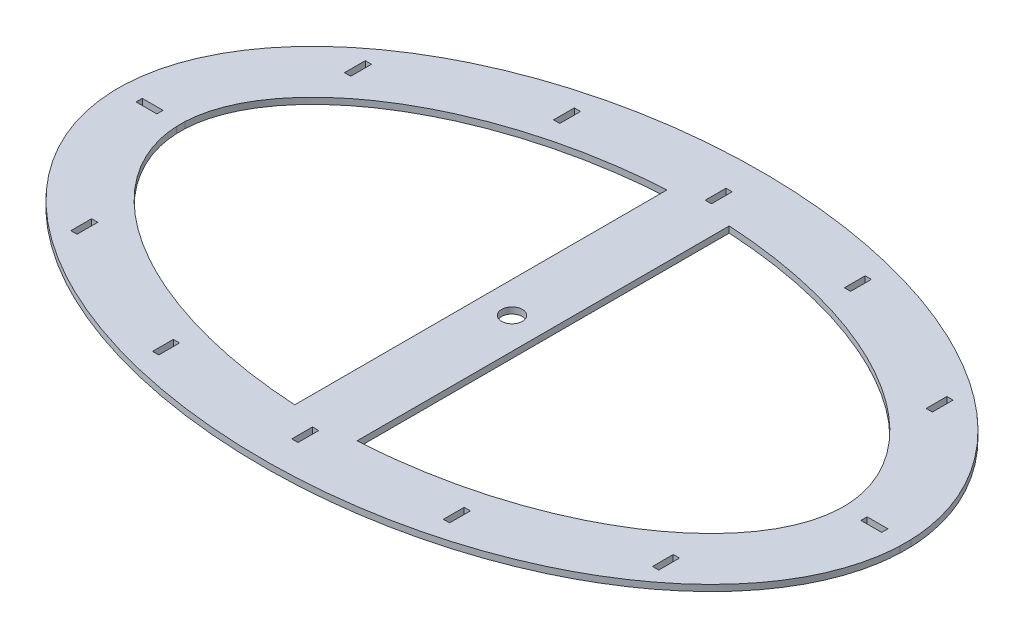
SolidWorks part; units mm, degrees
ref_plane "前视基准面" through (0, 0, 0) normal (0, 0, 1) x (1, 0, 0)
ref_plane "上视基准面" through (0, 0, 0) normal (0, 1, 0) x (1, 0, 0)
ref_plane "右视基准面" through (0, 0, 0) normal (1, 0, 0) x (0, 0, -1)
sketch "草图1" plane through (0, 0, 0) normal (0, 1, 0) x (1, 0, 0)
  line L0 (159.5, 2.0834) -> (159.5, -2.0834)
  line L1 (-189.5, 2.6781) -> (-189.5, -2.6781)
  line L2 (189.5, 2.6781) -> (189.5, -2.6781)
  line L3 (-159.5, 2.0834) -> (-159.5, -2.0834)
  line L6 (-15, -89.5841) -> (-15, 89.5841)
  line L8 (15, -89.5841) -> (15, 89.5841)
  circle A0 centre (0, 0) radius 5
  spline S0 degree 4 poles (-189.5, 2.6781) (-189.403, 5.4288) (-188.9135, 11.2804) (-187.1848, 20.477) (-182.9016, 32.5585) (-176.5181, 44.4734) (-168.3707, 55.661) (-158.8165, 65.9375) (-145.6224, 77.4085) (-128.2334, 89.1222) (-106.4053, 100.093) (-80.3284, 109.3456) (-53.4155, 115.7167) (-26.0125, 119.4067) (1.6122, 120.5267) (29.2235, 119.1102) (56.5842, 115.1149) (83.4196, 108.4201) (109.201, 98.8767) (130.5275, 87.757) (147.4252, 76.0011) (160.1728, 64.5989) (169.4507, 54.338) (177.4202, 43.0195) (183.4223, 31.3068) (187.3852, 19.5711) (188.9582, 10.7853) (189.4055, 5.3595) (189.5, 2.6781) knots 0 0 0 0 0 0.022605 0.04819 0.076526 0.104867 0.133209 0.161552 0.191528 0.248215 0.304901 0.361588 0.418275 0.474961 0.531648 0.588335 0.645021 0.701708 0.758395 0.813601 0.841944 0.870287 0.89863 0.926971 0.955318 0.977964 1 1 1 1 1 construction
  spline S1 degree 4 poles (-189.5, 2.6781) (-189.403, 5.4288) (-188.9135, 11.2804) (-187.1848, 20.477) (-182.9016, 32.5585) (-176.5181, 44.4734) (-168.3707, 55.661) (-158.8165, 65.9375) (-145.6224, 77.4085) (-128.2334, 89.1222) (-106.4053, 100.093) (-80.3284, 109.3456) (-53.4155, 115.7167) (-26.0125, 119.4067) (1.6122, 120.5267) (29.2235, 119.1102) (56.5842, 115.1149) (83.4196, 108.4201) (109.201, 98.8767) (130.5275, 87.757) (147.4252, 76.0011) (160.1728, 64.5989) (169.4507, 54.338) (177.4202, 43.0195) (183.4223, 31.3068) (187.3852, 19.5711) (188.9582, 10.7853) (189.4055, 5.3595) (189.5, 2.6781) knots 0 0 0 0 0 0.022605 0.04819 0.076526 0.104867 0.133209 0.161552 0.191528 0.248215 0.304901 0.361588 0.418275 0.474961 0.531648 0.588335 0.645021 0.701708 0.758395 0.813601 0.841944 0.870287 0.89863 0.926971 0.955318 0.977964 1 1 1 1 1
  spline S2 degree 4 poles (-189.5, -2.6781) (-189.403, -5.4288) (-188.9135, -11.2804) (-187.1848, -20.477) (-182.9016, -32.5585) (-176.5181, -44.4734) (-168.3707, -55.661) (-158.8165, -65.9375) (-145.6224, -77.4085) (-128.2334, -89.1222) (-106.4053, -100.093) (-80.3284, -109.3456) (-53.4155, -115.7167) (-26.0125, -119.4067) (1.6122, -120.5267) (29.2235, -119.1102) (56.5842, -115.1149) (83.4196, -108.4201) (109.201, -98.8767) (130.5275, -87.757) (147.4252, -76.0011) (160.1728, -64.5989) (169.4507, -54.338) (177.4202, -43.0195) (183.4223, -31.3068) (187.3852, -19.5711) (188.9582, -10.7853) (189.4055, -5.3595) (189.5, -2.6781) knots 0 0 0 0 0 0.022605 0.04819 0.076526 0.104867 0.133209 0.161552 0.191528 0.248215 0.304901 0.361588 0.418275 0.474961 0.531648 0.588335 0.645021 0.701708 0.758395 0.813601 0.841944 0.870287 0.89863 0.926971 0.955318 0.977964 1 1 1 1 1
  spline S3 degree 1 poles (-159.5, 2.0834) (159.5, 2.0834) knots 0 0 1 1 construction
  spline S4 degree 1 poles (-159.5, -2.0834) (159.5, -2.0834) knots 0 0 1 1 construction
  spline S5 degree 3 poles (-159.5, 2.0834) (-159.4304, 3.6198) (-159.1394, 6.6713) (-157.9407, 12.8162) (-155.2804, 20.5003) (-150.2462, 29.6305) (-141.2678, 41.3756) (-126.3637, 54.7415) (-104.5151, 67.8369) (-80.1382, 77.8661) (-54.1823, 84.9094) (-27.3041, 89.0816) (0, 90.4628) (27.3041, 89.0816) (54.1823, 84.9094) (80.1382, 77.8661) (104.5153, 67.8369) (126.3637, 54.7414) (141.2676, 41.3759) (150.2464, 29.6301) (155.2803, 20.5005) (157.9408, 12.816) (159.1394, 6.6715) (159.4304, 3.6198) (159.5, 2.0834) knots 0.001569 0.001569 0.001569 0.001569 0.017145 0.032721 0.063873 0.095025 0.126177 0.18848 0.250784 0.313088 0.375392 0.437696 0.5 0.562304 0.624608 0.686912 0.749216 0.81152 0.873823 0.904975 0.936127 0.967279 0.982855 0.998431 0.998431 0.998431 0.998431
  spline S6 degree 3 poles (159.5, -2.0834) (159.4304, -3.6198) (159.1394, -6.6715) (157.9408, -12.816) (155.2803, -20.5005) (150.2464, -29.6301) (141.2676, -41.3759) (126.3637, -54.7414) (104.5153, -67.8369) (80.1382, -77.8661) (54.1823, -84.9094) (27.3041, -89.0816) (0, -90.4628) (-27.3041, -89.0816) (-54.1823, -84.9094) (-80.1382, -77.8661) (-104.5151, -67.8369) (-126.3637, -54.7415) (-141.2678, -41.3756) (-150.2462, -29.6305) (-155.2804, -20.5003) (-157.9407, -12.8162) (-159.1394, -6.6713) (-159.4304, -3.6198) (-159.5, -2.0834) knots 0.001569 0.001569 0.001569 0.001569 0.017145 0.032721 0.063873 0.095025 0.126177 0.18848 0.250784 0.313088 0.375392 0.437696 0.5 0.562304 0.624608 0.686912 0.749216 0.81152 0.873823 0.904975 0.936127 0.967279 0.982855 0.998431 0.998431 0.998431 0.998431
  point P11 (0, 0)
  dimension "D1" = 30
extrude "凸台-拉伸1" add sketch "草图1" along normal blind 3 contours S6 L8 S5 L6 A0 | L1 S2 L2 S1 L0 S6 L3 S5
sketch "草图2" plane through (0, 3, 0) normal (0, 1, 0) x (1, 0, 0)
  line L1 (141.5, -70.874) -> (138.5, -70.874)
  line L2 (141.5, -70.874) -> (141.5, -60.874)
  line L3 (141.5, -60.874) -> (138.5, -60.874)
  line L4 (138.5, -70.874) -> (138.5, -60.874)
  line L5 (179.4735, -1.5024) -> (169.4735, -1.5024)
  line L6 (179.4735, -1.5024) -> (179.4735, 1.4976)
  line L7 (179.4735, 1.4976) -> (169.4735, 1.4976)
  line L8 (169.4735, -1.5024) -> (169.4735, 1.4976)
  line L9 (141.5, 60.8692) -> (138.5, 60.8692)
  line L10 (141.5, 60.8692) -> (141.5, 70.8692)
  line L11 (141.5, 70.8692) -> (138.5, 70.8692)
  line L12 (138.5, 60.8692) -> (138.5, 70.8692)
  line L13 (71.5, -101.514) -> (68.5, -101.514)
  line L14 (71.5, -101.514) -> (71.5, -91.514)
  line L15 (71.5, -91.514) -> (68.5, -91.514)
  line L16 (68.5, -101.514) -> (68.5, -91.514)
  line L17 (71.5, 91.5092) -> (68.5, 91.5092)
  line L18 (71.5, 91.5092) -> (71.5, 101.5092)
  line L19 (71.5, 101.5092) -> (68.5, 101.5092)
  line L20 (68.5, 91.5092) -> (68.5, 101.5092)
  line L21 (1.5, 94.5195) -> (-1.5, 94.5195)
  line L22 (1.5, 94.5195) -> (1.5, 104.5195)
  line L23 (1.5, 104.5195) -> (-1.5, 104.5195)
  line L24 (-1.5, 94.5195) -> (-1.5, 104.5195)
  line L25 (1.5, -104.5243) -> (-1.5, -104.5243)
  line L26 (1.5, -104.5243) -> (1.5, -94.5243)
  line L27 (1.5, -94.5243) -> (-1.5, -94.5243)
  line L28 (-1.5, -104.5243) -> (-1.5, -94.5243)
  line L29 (-68.5, -101.514) -> (-71.5, -101.514)
  line L30 (-68.5, -101.514) -> (-68.5, -91.514)
  line L31 (-68.5, -91.514) -> (-71.5, -91.514)
  line L32 (-71.5, -101.514) -> (-71.5, -91.514)
  line L33 (-138.5, -70.874) -> (-141.5, -70.874)
  line L34 (-138.5, -70.874) -> (-138.5, -60.874)
  line L35 (-138.5, -60.874) -> (-141.5, -60.874)
  line L36 (-141.5, -70.874) -> (-141.5, -60.874)
  line L37 (-169.4735, -1.5024) -> (-179.4735, -1.5024)
  line L38 (-169.4735, -1.5024) -> (-169.4735, 1.4976)
  line L39 (-169.4735, 1.4976) -> (-179.4735, 1.4976)
  line L40 (-179.4735, -1.5024) -> (-179.4735, 1.4976)
  line L41 (-141.5, 60.8692) -> (-138.5, 60.8692)
  line L42 (-141.5, 60.8692) -> (-141.5, 70.8692)
  line L43 (-141.5, 70.8692) -> (-138.5, 70.8692)
  line L44 (-138.5, 60.8692) -> (-138.5, 70.8692)
  line L45 (-68.5, 91.5092) -> (-71.5, 91.5092)
  line L46 (-68.5, 91.5092) -> (-68.5, 101.5092)
  line L47 (-68.5, 101.5092) -> (-71.5, 101.5092)
  line L48 (-71.5, 91.5092) -> (-71.5, 101.5092)
extrude "切除-拉伸1" cut sketch "草图2" against normal through all
